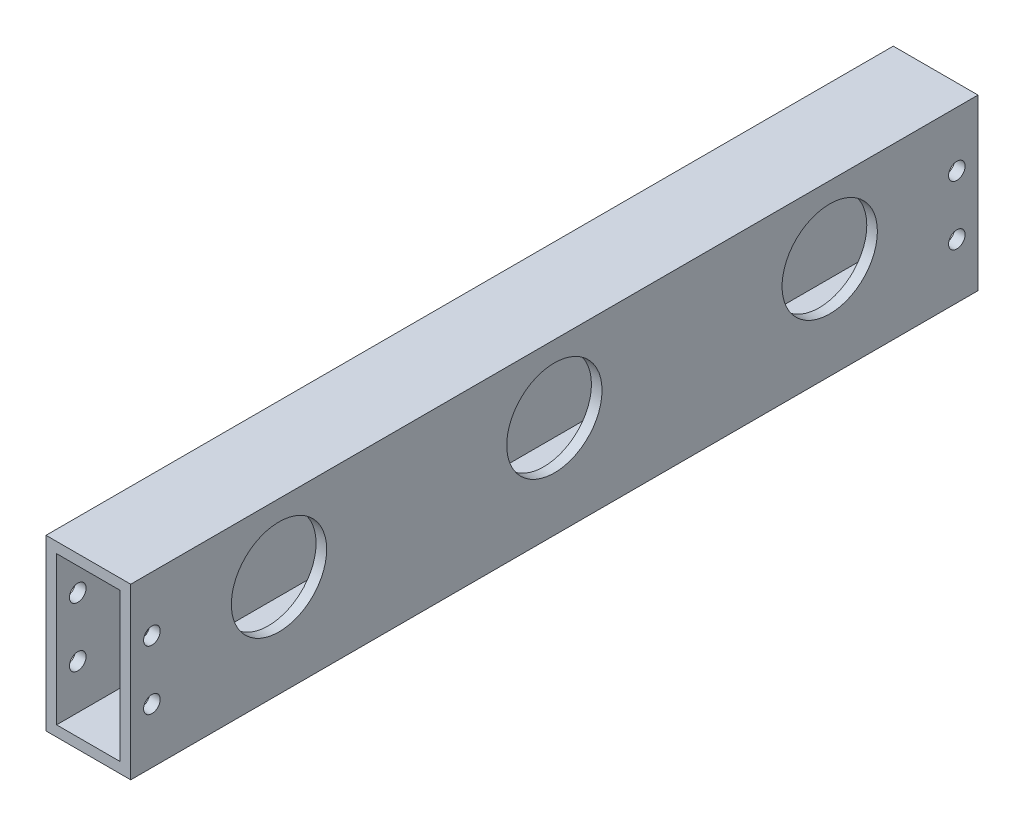
SolidWorks part; units mm, degrees
material "6061-T6 (SS)"
ref_plane "Front Plane" through (0, 0, 0) normal (0, 0, 1) x (1, 0, 0)
ref_plane "Top Plane" through (0, 0, 0) normal (0, 1, 0) x (1, 0, 0)
ref_plane "Right Plane" through (0, 0, 0) normal (1, 0, 0) x (0, 0, -1)
sketch "Sketch1" plane through (0, 0, 0) normal (1, 0, 0) x (0, 0, -1)
  line L1 (-127, 25.4) -> (127, 25.4)
  line L2 (-127, 25.4) -> (-127, -25.4)
  line L3 (-127, -25.4) -> (127, -25.4)
  line L4 (127, 25.4) -> (127, -25.4)
  line L5 (-127, 25.4) -> (127, -25.4) construction
  line L6 (-127, -25.4) -> (127, 25.4) construction
  point P0 (0, 0)
  dimension "D1" = 50.8
  dimension "D2" = 254
extrude "Boss-Extrude1" add sketch "Sketch1" along normal blind 25.4
shell "Shell1" thickness 3.175
sketch "Sketch2" plane through (25.4, 0, 0) normal (1, 0, 0) x (0, 0, -1)
  line L0 (-127, -25.4) -> (127, -25.4) construction
  circle A0 centre (0, 5.08) radius 14.2875
  circle A1 centre (-82.55, 5.08) radius 14.2875
  circle A2 centre (82.55, 5.08) radius 14.2875
  circle A3 centre (-82.55, 5.08) radius 38.1 construction
  circle A4 centre (0, 5.08) radius 38.1 construction
  circle A5 centre (82.55, 5.08) radius 38.1 construction
  point P11 (0, 0)
  dimension "D1" = 28.575
  dimension "D5" = 76.2
  dimension "D2" = 30.48
  dimension "D3" = 82.55
  dimension "D4" = 82.55
  dimension "D6" = 0
extrude "Cut-Extrude1" cut sketch "Sketch2" against normal through all
sketch "Sketch3" plane through (25.4, 0, 0) normal (1, 0, 0) x (0, 0, -1)
  line L0 (-120.65, 8.89) -> (-120.65, -8.89) construction
  line L1 (-127, 25.4) -> (-127, -25.4) construction
  point P2 (-120.65, 0)
  point P3 (-127, 0)
  dimension "D1" = 17.78
  dimension "D2" = 6.35
hole_wizard "#10 Clearance Hole1" positions "Sketch4" profile "Sketch6" hole size "#10" standard "ANSI Inch" end condition through all
sketch "Sketch4" plane through (25.4, 0, 0) normal (1, 0, 0) x (0, 0, -1)
  point P0 (-120.65, 8.89)
  point P3 (-120.65, -8.89)
sketch "Sketch6" plane through (25.4, 8.89, 120.65) normal (0, 1, 0) x (0, 0, -1)
  line L0 (0, 0) -> (0, 25.4)
  line L1 (0, 25.4) -> (2.4892, 25.4)
  line L2 (2.4892, 25.4) -> (2.4892, 0)
  line L5 (2.4892, 0) -> (0, 0)
  line L11 (0, -6.35) -> (0, 107.95) construction
  dimension "Thru Hole Dia." = 4.9784
  dimension "Thru Hole Depth" = 25.4
mirror "Mirror1" about plane through (0, 0, 0) normal (0, 0, 1) of "#10 Clearance Hole1"
